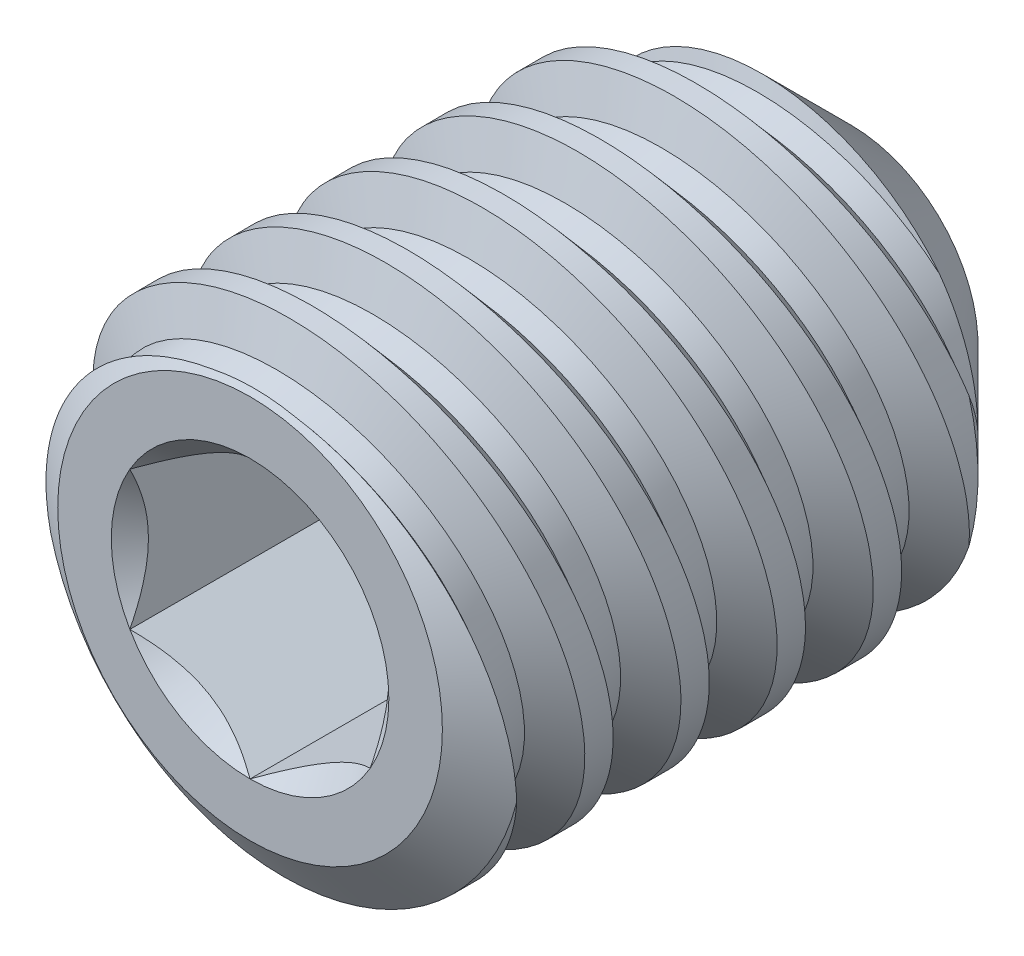
SolidWorks part; units mm, degrees
ref_plane "Front" through (0, 0, 0) normal (0, 0, 1) x (1, 0, 0)
ref_plane "Top" through (0, 0, 0) normal (0, 1, 0) x (1, 0, 0)
ref_plane "Right" through (0, 0, 0) normal (1, 0, 0) x (0, 0, -1)
sketch "Sketch22" plane through (0, 0, 0) normal (1, 0, 0) x (0, 0, -1)
  line L0 (0, 0) -> (0, 2.54)
  line L1 (0, 2.54) -> (0.4446, 3.175)
  line L2 (0.4446, 3.175) -> (6.4389, 3.175)
  line L3 (6.4389, 3.175) -> (7.9375, 1.6764)
  line L4 (7.9375, 1.6764) -> (6.9302, 0)
  line L5 (6.9302, 0) -> (0, 0)
  line L6 (6.9302, 0) -> (7.9375, 0) construction
  line L7 (7.9375, 0) -> (7.9375, 1.6764) construction
  line L8 (7.9375, -1.6764) -> (6.9302, 0) construction
  line L9 (0.4446, -3.175) -> (6.4389, -3.175) construction
  dimension "Screw Dia" = 6.35
  dimension "Length" = 7.9375
  dimension "D3" = 35
  dimension "Cup Point Dia" = 3.3528
  dimension "D5" = 118
  dimension "D6" = 45
  dimension "D7" = 5.08
revolve "Revolve1" add sketch "Sketch22" angle 360 about L6
sketch "Sketch6" plane through (0, 0, 0) normal (1, 0, 0) x (0, 0, -1)
  line L0 (4.4404, 3.175) -> (5.7104, -3.175) construction
  line L1 (0.4446, 3.175) -> (6.4389, 3.175) construction
  line L2 (0.4446, -3.175) -> (6.4389, -3.175) construction
  line L3 (4.4404, 3.175) -> (4.596, 3.2061) construction
  line L4 (5.4314, 2.6722) -> (5.12, 2.6099)
  line L5 (5.12, 2.6099) -> (4.596, 3.2061)
  line L6 (5.4314, 2.6722) -> (5.6857, 3.4241)
  line L7 (5.6857, 3.4241) -> (4.596, 3.2061)
  line L8 (5.1689, 3.175) -> (6.4389, -3.175) construction
  line L9 (7.1674, 0.2727) -> (4.4404, -0.2727) construction
  line L10 (5.1409, 3.3151) -> (5.2757, 2.641) construction
  line L13 (4.4404, -3.175) -> (4.4404, 3.175) construction
  line L14 (4.4404, -3.175) -> (5.7104, -3.175) construction
  line L15 (5.7104, -3.175) -> (6.4389, -3.175) construction
  line L18 (4.4404, 3.175) -> (5.1689, 3.175) construction
  point P18 (5.8039, 0)
  dimension "D1" = 1.27
  dimension "D2" = 0.3175
  dimension "D3" = 60
  dimension "D4" = 0.1588
  dimension "Pitch" = 1.27
revolve "Cut-Revolve8" cut sketch "Sketch6" angle 360 about L9
pattern_linear "LPattern1" count 5 spacing 1.27 along (0, 0, 1) count 2 spacing 1.27 along (0, 0, -1) of "Cut-Revolve8"
sketch "Sketch23" plane through (0, 0, 0) normal (0, 0, 1) x (1, 0, 0)
  line L1 (0, 1.8331) -> (-1.5875, 0.9165)
  line L2 (-1.5875, 0.9165) -> (-1.5875, -0.9165)
  line L3 (-1.5875, -0.9165) -> (0, -1.8331)
  line L4 (0, -1.8331) -> (1.5875, -0.9165)
  line L5 (1.5875, -0.9165) -> (1.5875, 0.9165)
  line L6 (1.5875, 0.9165) -> (0, 1.8331)
  circle A0 centre (0, 0) radius 1.5875 construction
  dimension "Hex" = 3.175
extrude "Cut-Extrude10" cut sketch "Sketch23" against normal blind 3.175
sketch "Sketch24" plane through (0, 0, 0) normal (0, 0, 1) x (1, 0, 0)
  circle A0 centre (0, 0) radius 1.8331
extrude "Cut-Extrude11" cut sketch "Sketch24" against normal through all draft 45
sketch "Sketch26" plane through (0, 0, -3.175) normal (0, 0, 1) x (1, 0, 0)
  circle A0 centre (0, 0) radius 1.5875 construction
  circle A1 centre (0, 0) radius 1.5875
extrude "Cut-Extrude12" cut sketch "Sketch26" against normal through all draft 59
sketch "Sketch21" plane through (0, 0, 0) normal (1, 0, 0) x (0, 0, -1)
  line L0 (2.5781, 2.3812) -> (2.5781, -2.3812) construction
  line L1 (2.5781, -2.3812) -> (6.3881, -2.3812) construction
  line L2 (6.3881, -2.3812) -> (6.3881, 2.3812) construction
  line L4 (6.3881, 2.3812) -> (2.5781, 2.3812) construction
  line L5 (2.5781, 0) -> (0, 0) construction
  line L6 (2.7686, 1.9737) -> (6.1976, 1.9737) construction
  line L7 (2.7686, -1.9737) -> (6.1976, -1.9737) construction
  arc A0 (2.7686, 1.9737) -> (2.7686, -1.9737) centre (12.8976, 0) ccw
  arc A1 (6.1976, 1.9737) -> (6.1976, -1.9737) centre (-3.9314, 0) cw
  arc A2 (2.7686, 1.9737) -> (6.1976, 1.9737) centre (4.4831, -1.4287) cw
  arc A3 (2.7686, -1.9737) -> (6.1976, -1.9737) centre (4.4831, 1.4288) ccw
  dimension "D2" = 4.7625
  dimension "D3" = 0.0508
  dimension "D1" = 3.81
  dimension "D4" = 3.81
  dimension "D5" = 3.429
equation "\"D2@Sketch6\"=\"Pitch@Sketch6\"/4"
equation "\"D4@Sketch6\"=\"Pitch@Sketch6\"/8"
equation "\"D1@Sketch6\"=\"Pitch@Sketch6\""
equation "\"D3@LPattern1\"=\"Pitch@Sketch6\""
equation "\"D1@LPattern1\"=(\"Length@Sketch22\"/\"Pitch@Sketch6\")-1"
equation "\"D4@LPattern1\"=\"Pitch@Sketch6\""
equation "\"D7@Sketch22\"=\"Screw Dia@Sketch22\"*.8"
equation "\"D1@Sketch21\"=\"Pitch@Sketch6\"*3"
equation "\"D2@Sketch21\"=\"Screw Dia@Sketch22\"*.75"
equation "\"D4@Sketch21\"=\"D1@Sketch21\""
equation "\"D5@Sketch21\"=\"D1@Sketch21\"*.9"
